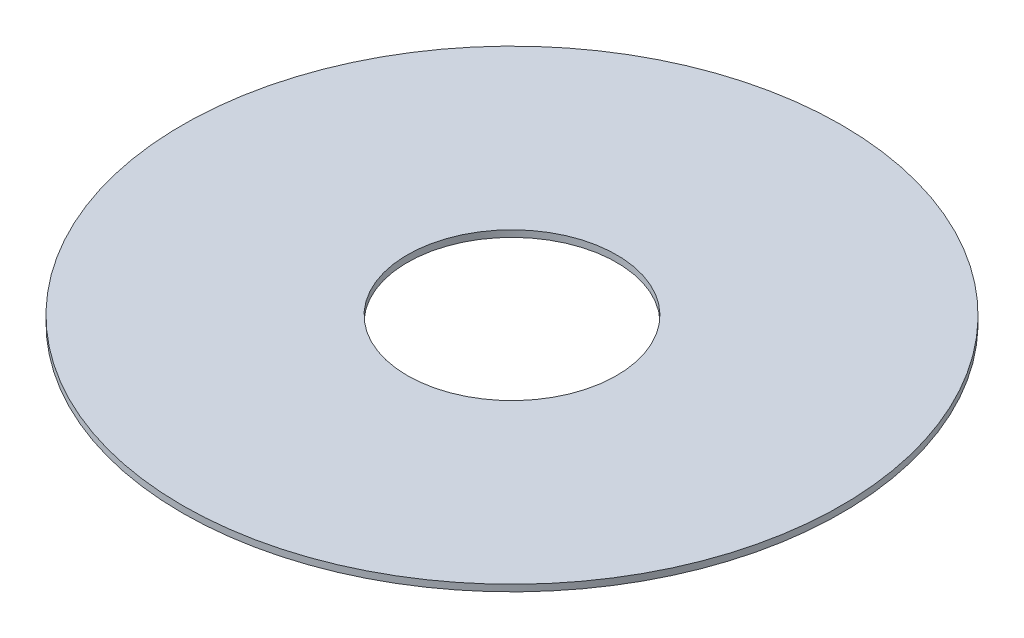
SolidWorks part; units mm, degrees
ref_plane "Front Plane" through (0, 0, 0) normal (0, 0, 1) x (1, 0, 0)
ref_plane "Top Plane" through (0, 0, 0) normal (0, 1, 0) x (1, 0, 0)
ref_plane "Right Plane" through (0, 0, 0) normal (1, 0, 0) x (0, 0, -1)
sketch "Sketch1" plane through (0, 0, 0) normal (0, 1, 0) x (1, 0, 0)
  circle A0 centre (0, 0) radius 31.75
  circle A1 centre (0, 0) radius 100
  dimension "D1" = 200
  dimension "D2" = 63.5
extrude "Boss-Extrude1" add sketch "Sketch1" along normal blind 2
